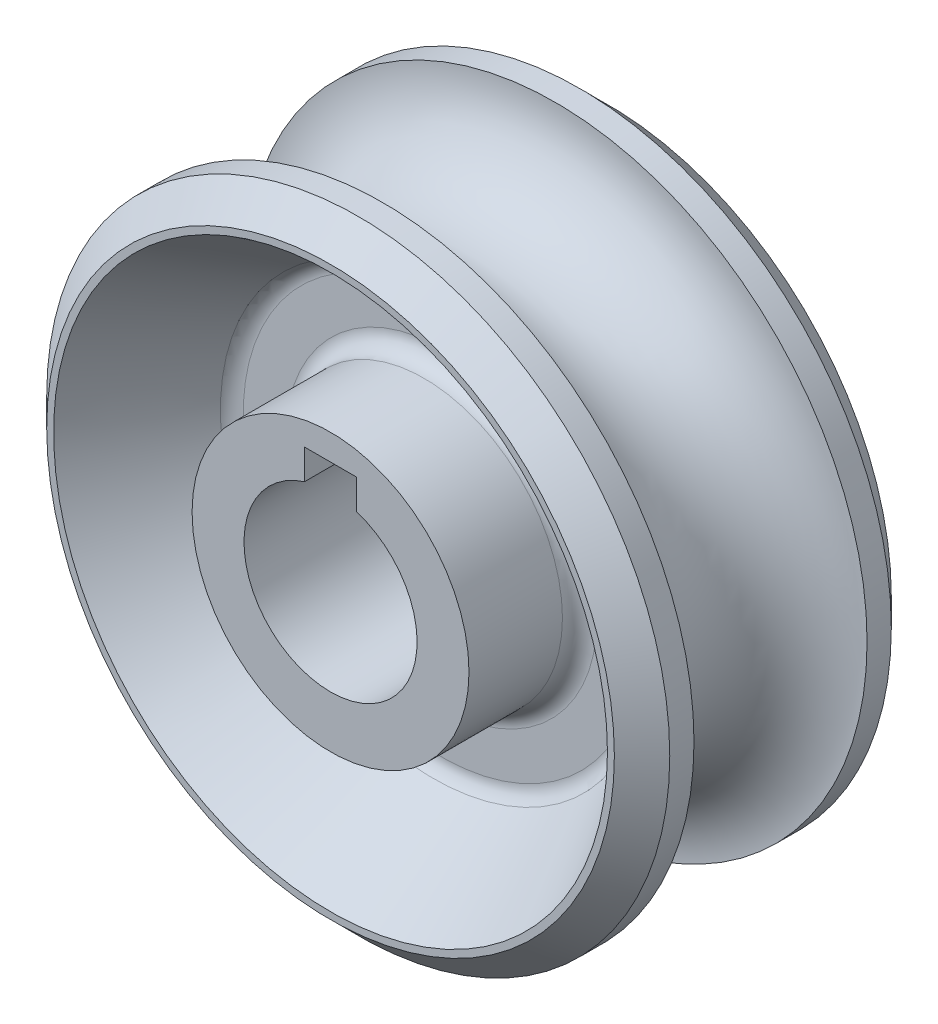
SolidWorks part; units mm, degrees
material "AISI 1020"
ref_plane "Front Plane" through (0, 0, 0) normal (0, 0, 1) x (1, 0, 0)
ref_plane "Top Plane" through (0, 0, 0) normal (0, 1, 0) x (1, 0, 0)
ref_plane "Right Plane" through (0, 0, 0) normal (1, 0, 0) x (0, 0, -1)
sketch "Base Sketch" plane through (0, 0, 0) normal (0, 0, 1) x (1, 0, 0)
  circle A0 centre (0, 0) radius 28.575
  circle A1 centre (0, 0) radius 7.9375
  dimension "D1" = 57.15
  dimension "D2" = 15.875
extrude "Base" add sketch "Base Sketch" along normal mid plane 25.4
sketch "Groove Sketch" plane through (0, 0, 0) normal (1, 0, 0) x (0, 0, -1)
  line L0 (12.7, 28.575) -> (-12.7, 28.575) construction
  line L1 (0, 0) -> (25.0554, 0) construction
  circle A0 centre (0, 28.575) radius 7.9375
  dimension "D1" = 15.875
revolve "Groove" cut sketch "Groove Sketch" angle 360 about L1
sketch "Inner Sketch" plane through (0, 0, 0) normal (1, 0, 0) x (0, 0, -1)
  line L0 (12.7, 12.7) -> (2.54, 12.7)
  line L1 (12.7, -28.575) -> (12.7, 28.575) construction
  line L2 (2.54, 12.7) -> (2.54, 19.05)
  line L3 (2.54, 19.05) -> (12.7, 25.4)
  line L4 (12.7, 25.4) -> (12.7, 12.7)
  line L5 (0, 0) -> (27.599, 0) construction
  line L6 (0, 0) -> (0, 38.1046) construction
  line L7 (-12.7, 25.4) -> (-12.7, 12.7)
  line L8 (-12.7, 12.7) -> (-2.54, 12.7)
  line L9 (-2.54, 12.7) -> (-2.54, 19.05)
  line L10 (-2.54, 19.05) -> (-12.7, 25.4)
  dimension "D1" = 6.35
  dimension "D2" = 10.16
  dimension "D3" = 50.8
  dimension "D4" = 25.4
revolve "Inner Revolved Cut" cut sketch "Inner Sketch" angle 360 about L5
chamfer "Outer Chamfer" distance 2.54 angle 45 2 edges at (28.575, 0, -12.7) (28.575, 0, 12.7)
fillet "Inner Fillet" radius 1.5875 4 edges at (19.05, 0, -2.54) (12.7, 0, -2.54) (12.7, 0, 2.54) (19.05, 0, 2.54)
sketch "Keyway Sketch" plane through (0, 0, 0) normal (0, 0, 1) x (1, 0, 0)
  line L1 (2.3876, 0) -> (-2.3876, 0)
  line L2 (2.3876, 0) -> (2.3876, 10.3251)
  line L3 (2.3876, 10.3251) -> (-2.3876, 10.3251)
  line L4 (-2.3876, 0) -> (-2.3876, 10.3251)
  line L5 (2.3876, 0) -> (-2.3876, 10.3251) construction
  line L6 (2.3876, 10.3251) -> (-2.3876, 0) construction
  circle A1 centre (0, 0) radius 7.9375 construction
  point P0 (0, 5.1626)
  dimension "D1" = 4.7752
  dimension "D2" = 2.3876
extrude "Keyway" cut sketch "Keyway Sketch" against normal through all and the other way through all
